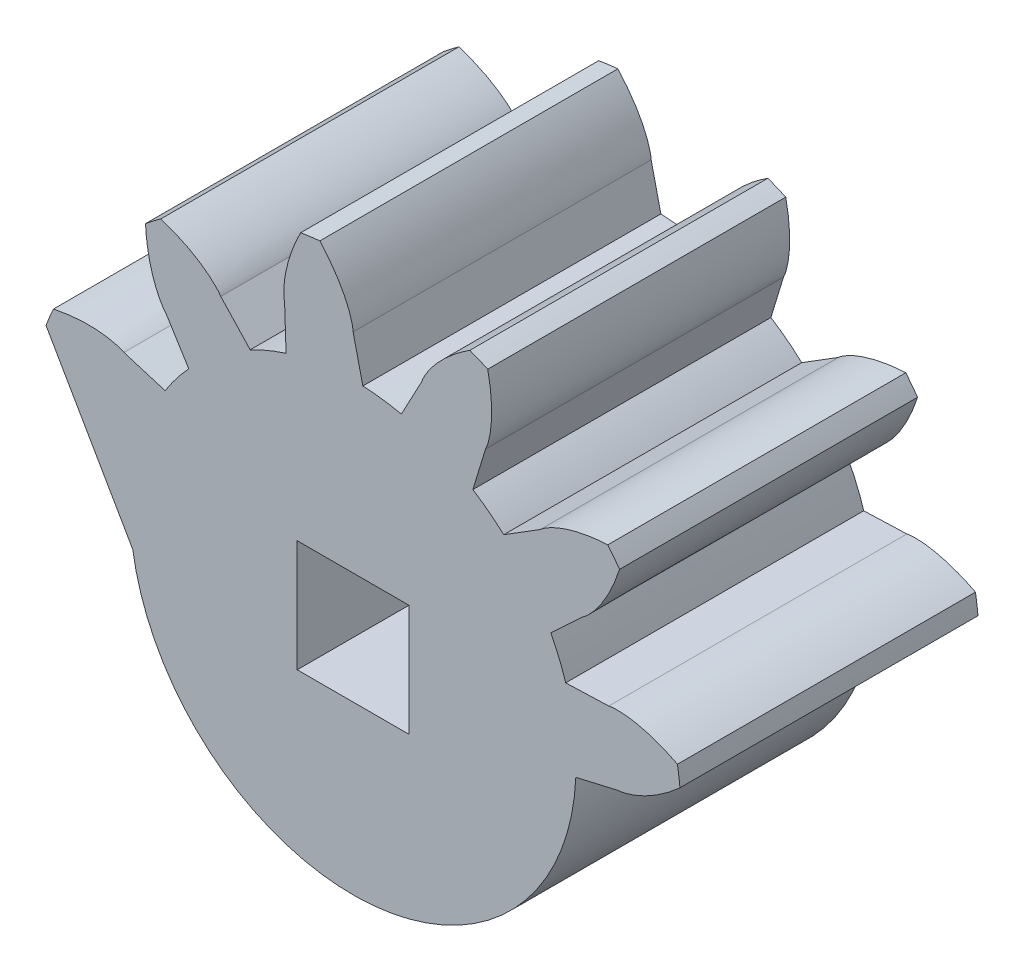
SolidWorks part; units mm, degrees
material "PE High Density"
ref_plane "Front Plane" through (0, 0, 0) normal (0, 0, 1) x (1, 0, 0)
ref_plane "Top Plane" through (0, 0, 0) normal (0, 1, 0) x (1, 0, 0)
ref_plane "Right Plane" through (0, 0, 0) normal (1, 0, 0) x (0, 0, -1)
sketch "Sketch1" plane through (0, 0, 0) normal (0, 0, 1) x (1, 0, 0)
  line L1 (-2.3813, -2.3813) -> (2.3812, -2.3813)
  line L2 (-2.3813, -2.3813) -> (-2.3813, 2.3813)
  line L3 (-2.3813, 2.3813) -> (2.3812, 2.3813)
  line L4 (2.3812, -2.3813) -> (2.3812, 2.3813)
  line L5 (-2.3813, -2.3813) -> (2.3812, 2.3813) construction
  line L6 (-2.3813, 2.3813) -> (2.3812, -2.3813) construction
  circle A1 centre (0, 0) radius 14
  dimension "D2" = 28
  dimension "D3" = 4.7625
  dimension "D4" = 4.7625
extrude "Boss-Extrude1" add sketch "Sketch1" along normal blind 12.7
sketch "Sketch2" plane through (0, 0, 12.7) normal (0, 0, 1) x (1, 0, 0)
  line L0 (0, 0) -> (11.2765, 0) construction
  line L1 (2.3812, -2.3813) -> (2.3812, 2.3813) construction
  line L2 (2.3812, 2.3813) -> (-2.3813, 2.3813) construction
  line L3 (0, 0) -> (10.8923, 2.9186) construction
  line L4 (0, 0) -> (11.18, 1.4719) construction
  line L5 (9.7657, 5.6383) -> (8.4258, 4.386)
  line L6 (0, 0) -> (10.4181, 4.3153) construction
  line L7 (10.8923, 2.9186) -> (9.0593, 2.8565)
  circle A0 centre (0, 0) radius 9.499 construction
  arc A1 (13.8485, 2.2209) -> (11.3628, 8.222) centre (0, 0) ccw construction
  circle A2 centre (0, 0) radius 12 construction
  circle A3 centre (0, 0) radius 11.2765 construction
  arc A6 (13.8485, 2.2209) -> (11.3628, 8.222) centre (0, 0) ccw
  arc A7 (9.0593, 2.8565) -> (8.4258, 4.386) centre (0, 0) ccw
  spline S2 degree 4 poles (10.8923, 2.9186) (10.9262, 2.9261) (11.0223, 2.9427) (11.2081, 2.956) (11.5106, 2.9512) (11.9002, 2.906) (12.3936, 2.803) (12.9533, 2.6288) (13.387, 2.4493) (13.6975, 2.2991) (13.8485, 2.2209) knots 0 0 0 0 0 0.005604 0.015718 0.02996 0.048734 0.068727 0.096889 0.124316 0.124316 0.124316 0.124316 0.124316
  spline S3 degree 4 poles (9.7657, 5.6383) (9.7951, 5.6569) (9.8747, 5.7131) (10.0155, 5.8351) (10.226, 6.0524) (10.4696, 6.3599) (10.7457, 6.7816) (11.0182, 7.3005) (11.198, 7.7341) (11.3113, 8.0599) (11.3628, 8.222) knots 0 0 0 0 0 0.005604 0.015718 0.02996 0.048734 0.068727 0.096889 0.124316 0.124316 0.124316 0.124316 0.124316
  dimension "D1" = 18.998
  dimension "D2" = 28.051
  dimension "D3" = 22.553
  dimension "D4" = 24
  dimension "D5" = 15
  dimension "D8" = 22.5
  dimension "D6" = 7.5
extrude "Cut-Extrude2" cut sketch "Sketch2" against normal blind 12.7
pattern_circular "CirPattern1" count 12 over 360 about axis through (0, 0, 12.7) along (0, 0, -1) of "Cut-Extrude2"
sketch "Sketch4" plane through (0, 0, 12.7) normal (0, 0, 1) x (1, 0, 0)
  line L0 (-9.4314, 1.1308) -> (-13.9004, 1.6667)
  line L1 (9.4349, -1.1021) -> (13.9055, -1.6243)
  arc A0 (-9.4314, 1.1308) -> (9.4349, -1.1021) centre (0, 0) ccw
  arc A1 (-13.9004, 1.6667) -> (13.9055, -1.6243) centre (0, 0) ccw
extrude "Cut-Extrude3" cut sketch "Sketch4" against normal blind 12.7
sketch "Sketch5" plane through (0, 0, 12.7) normal (0, 0, 1) x (1, 0, 0)
  line L0 (-9.3894, -1.4451) -> (-13.0865, 4.9743)
  line L1 (-4.2343, -2.9004) -> (-9.3894, -1.4451)
  line L2 (-4.9886, 1.2063) -> (-13.0865, 4.9743)
  arc A2 (-4.9886, 1.2063) -> (-4.2343, -2.9004) centre (0, 0) ccw
extrude "Boss-Extrude2" add sketch "Sketch5" against normal blind 12.7
sketch "Sketch6" plane through (0, 0, 12.7) normal (0, 0, 1) x (1, 0, 0)
  line L0 (0, 0) -> (0, 30.8078) construction
  line L1 (0, 0) -> (8.891, 33.1816) construction
  line L2 (0, 0) -> (1.6835, 11.8813) construction
  circle A0 centre (0, 0) radius 9.499
  circle A1 centre (0, 0) radius 14.0255
  circle A2 centre (0, 0) radius 12
  circle A3 centre (0, 0) radius 11.2765
  circle A4 centre (5.909, 9.6043) radius 4.8
  dimension "D1" = 18.998
  dimension "D2" = 28.051
  dimension "D3" = 22.553
  dimension "D4" = 24
  dimension "D6" = 9.6
  dimension "D5" = 15
  dimension "D7" = 1.449
